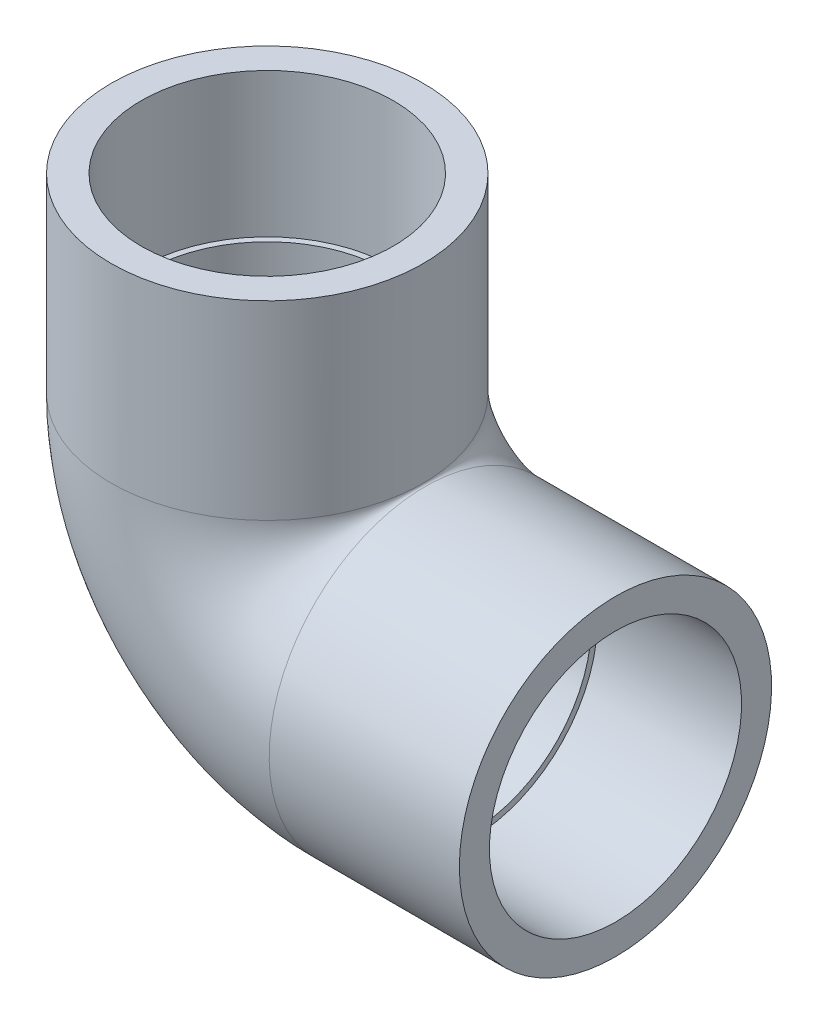
SolidWorks part; units mm, degrees
ref_plane "Front Plane" through (0, 0, 0) normal (0, 0, 1) x (1, 0, 0)
ref_plane "Top Plane" through (0, 0, 0) normal (0, 1, 0) x (1, 0, 0)
ref_plane "Right Plane" through (0, 0, 0) normal (1, 0, 0) x (0, 0, -1)
sketch "Sketch1" plane through (0, 0, 0) normal (0, 1, 0) x (1, 0, 0)
  circle A0 centre (0, 0) radius 20.6375
  circle A1 centre (0, 0) radius 15.875
  dimension "D1" = 41.275
  dimension "D2" = 31.75
sketch "Sketch2" plane through (0, 0, 0) normal (0, 0, 1) x (1, 0, 0)
  line L0 (0, 0) -> (0, -25.146)
  line L1 (20.8915, -25.146) -> (20.8915, -46.0375) construction
  line L2 (20.8915, -46.0375) -> (46.0375, -46.0375)
  line L3 (0, 0) -> (-20.6375, 0) construction
  line L5 (20.6375, 0) -> (-20.6375, 0) construction
  arc A0 (20.8915, -46.0375) -> (0, -25.146) centre (20.8915, -25.146) cw
  point P4 (-20.6375, 0)
  dimension "D1" = 25.146
  dimension "D2" = 66.675
sweep "Sweep3" add profiles "Sketch1" path "Sketch2"
sketch "Sketch3" plane through (46.0375, 0, 0) normal (1, 0, 0) x (0, 0, -1)
  line L0 (0, -46.0375) -> (0, -29.3687) construction
  circle A0 centre (0, -46.0375) radius 16.6687
  circle A1 centre (0, -46.0375) radius 15.875 construction
  dimension "D1" = 33.3375
extrude "Cut-Extrude1" cut sketch "Sketch3" against normal blind 19.05
sketch "Sketch5" plane through (0, 0, 0) normal (0, 1, 0) x (1, 0, 0)
  line L0 (0, 0) -> (0, -16.6687) construction
  circle A0 centre (0, 0) radius 16.6687
  dimension "D1" = 33.3375
extrude "Cut-Extrude2" cut sketch "Sketch5" against normal blind 19.05
